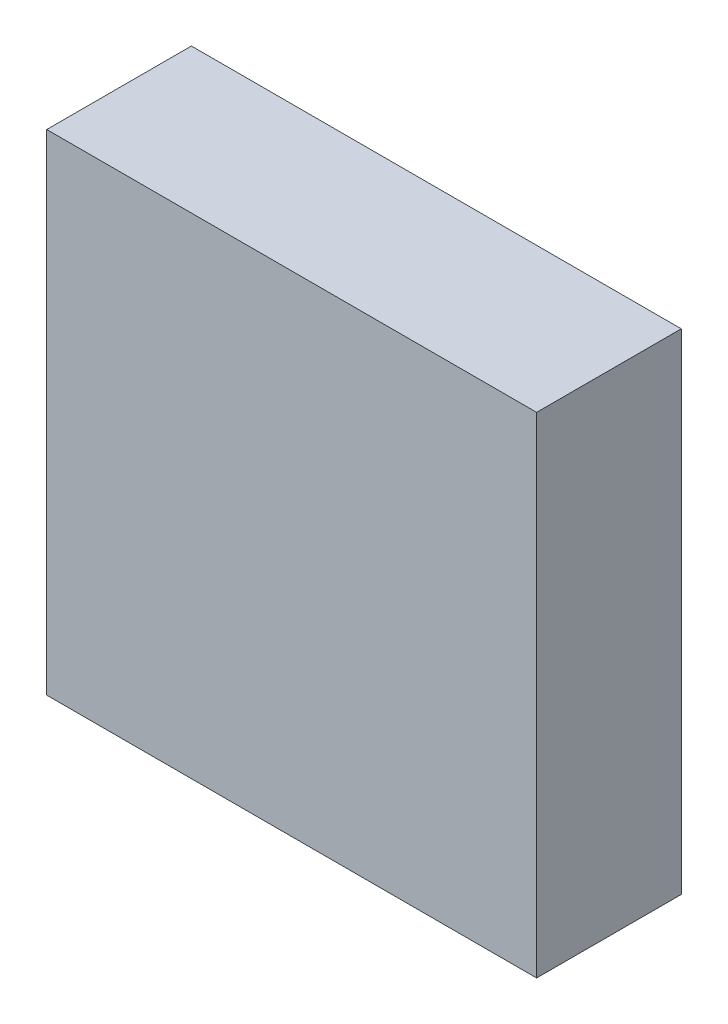
SolidWorks part; units mm, degrees
ref_plane "Front Plane" through (0, 0, 0) normal (0, 0, 1) x (1, 0, 0)
ref_plane "Top Plane" through (0, 0, 0) normal (0, 1, 0) x (1, 0, 0)
ref_plane "Right Plane" through (0, 0, 0) normal (1, 0, 0) x (0, 0, -1)
sketch "Sketch1" plane through (0, 0, 0) normal (0, 0, 1) x (1, 0, 0)
  line L1 (-224.3421, 272.5059) -> (283.6579, 272.5059)
  line L2 (-224.3421, 272.5059) -> (-224.3421, -235.4941)
  line L3 (-224.3421, -235.4941) -> (283.6579, -235.4941)
  line L4 (283.6579, 272.5059) -> (283.6579, -235.4941)
  point P4 (283.6579, -216.6401)
  dimension "D1" = 508
  dimension "D2" = 508
extrude "Boss-Extrude1" add sketch "Sketch1" along normal blind 150
